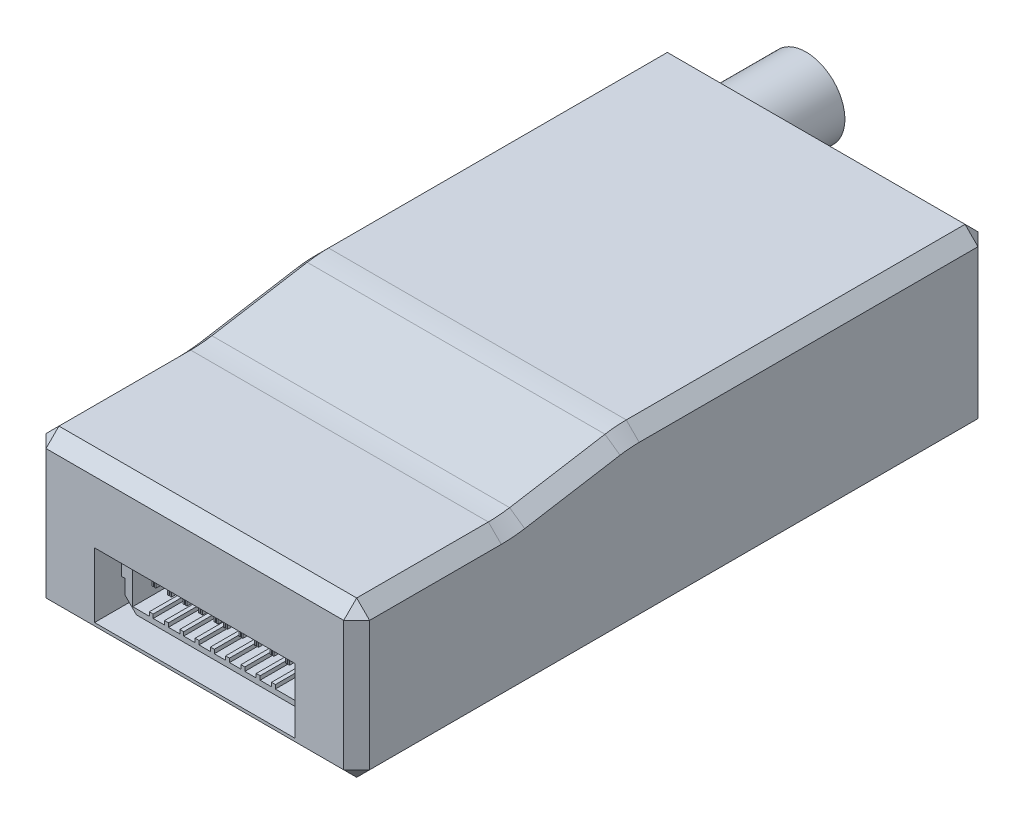
SolidWorks part; units mm, degrees
ref_plane "Front Plane" through (0, 0, 0) normal (0, 0, 1) x (1, 0, 0)
ref_plane "Top Plane" through (0, 0, 0) normal (0, 1, 0) x (1, 0, 0)
ref_plane "Right Plane" through (0, 0, 0) normal (1, 0, 0) x (0, 0, -1)
sketch "Sketch3" plane through (0, 0, 0) normal (1, 0, 0) x (0, 0, -1)
  line L0 (0, 0) -> (-49, 0)
  line L1 (0, 0) -> (0, 13.5)
  line L2 (-49, 0) -> (-49, 12)
  line L3 (-49, 12) -> (-37.8276, 12)
  line L4 (0, 13.5) -> (-27.1724, 13.5)
  line L5 (-36.1836, 12.1361) -> (-28.8164, 13.3639)
  arc A0 (-37.8276, 12) -> (-36.1836, 12.1361) centre (-37.8276, 22) ccw
  arc A1 (-27.1724, 13.5) -> (-28.8164, 13.3639) centre (-27.1724, 3.5) ccw
  point P9 (-37, 12)
  point P12 (-28, 13.5)
  dimension "D6" = 10
  dimension "D7" = 10
  dimension "D1" = 49
  dimension "D2" = 13.5
  dimension "D3" = 12
  dimension "D4" = 12
  dimension "D5" = 28
extrude "Boss-Extrude1" add sketch "Sketch3" along normal blind 25
chamfer "Chamfer1" distance 1 angle 45 20 edges at (0, 13.5, 13.5862) (25, 13.5, 13.5862) (0, 13.4659, 27.9972) (25, 13.4659, 27.9972) (0, 12.75, 32.5) (25, 12.75, 32.5) (0, 12.0341, 37.0028) (25, 12.0341, 37.0028) (12.5, 0, 0) (25, 6.75, 0) (12.5, 13.5, 0) (0, 6.75, 0) (0, 0, 24.5) (0, 12, 43.4138) (25, 0, 24.5) (25, 12, 43.4138) (12.5, 0, 49) (25, 6, 49) (0, 6, 49) (12.5, 12, 49)
sketch "Sketch4" plane through (0, 0, 49) normal (0, 0, 1) x (1, 0, 0)
  line L0 (12.5, 11) -> (12.5, 1) construction
  line L1 (24, 11) -> (1, 11) construction
  line L2 (1, 1) -> (24, 1) construction
  line L3 (4.75, 6.2316) -> (20.25, 6.2316)
  line L4 (20.25, 6.2316) -> (20.25, 1.2316)
  line L5 (20.25, 1.2316) -> (4.75, 1.2316)
  line L6 (4.75, 6.2316) -> (4.75, 1.2316)
  point P11 (12.5, 1.2316)
  point P12 (12.5, 6.2316)
  dimension "D1" = 15.5
  dimension "D2" = 5
extrude "Cut-Extrude1" cut sketch "Sketch4" against normal blind 10
sketch "Sketch5" plane through (0, 0, 39) normal (0, 0, 1) x (1, 0, 0)
  line L0 (12.5, 6.2316) -> (12.5, 1.2316) construction
  line L1 (20.25, 6.2316) -> (4.75, 6.2316) construction
  line L2 (4.75, 1.2316) -> (20.25, 1.2316) construction
  line L3 (20.1864, 6.1621) -> (4.8136, 6.1621)
  line L4 (8.1, 6.0621) -> (16.9, 6.0621)
  line L5 (16.9, 6.0621) -> (16.9, 4.5621)
  line L6 (19.0113, 1.3621) -> (19.9, 2.2507)
  line L7 (19.9, 2.2507) -> (19.9, 3.3621)
  line L8 (19.0113, 1.3621) -> (5.9887, 1.3621)
  line L9 (16.9, 4.5621) -> (15.5169, 4.5621)
  line L10 (15.5169, 4.5621) -> (15.0305, 4.7621)
  line L11 (15.0305, 4.7621) -> (9.9695, 4.7621)
  line L20 (19.9, 3.3621) -> (20.1864, 3.3621)
  line L21 (17.25, 5.6802) -> (18.25, 5.6802)
  line L22 (17.25, 5.6802) -> (17.25, 5.1302)
  line L23 (17.25, 5.1302) -> (18.25, 5.1302)
  line L24 (18.25, 5.6802) -> (18.25, 5.1302)
  line L25 (17.25, 5.6802) -> (18.25, 5.1302) construction
  line L26 (17.25, 5.1302) -> (18.25, 5.6802) construction
  line L31 (19.65, 5.1245) -> (18.65, 5.1245)
  line L32 (19.65, 5.1245) -> (19.65, 5.6745)
  line L33 (19.65, 5.6745) -> (18.65, 5.6745)
  line L34 (18.65, 5.1245) -> (18.65, 5.6745)
  line L35 (19.65, 5.1245) -> (18.65, 5.6745) construction
  line L36 (19.65, 5.6745) -> (18.65, 5.1245) construction
  line L37 (20.1864, 3.3621) -> (20.1864, 6.1621)
  line L38 (5.9887, 1.3621) -> (5.1, 2.2507)
  line L39 (5.1, 2.2507) -> (5.1, 3.3621)
  line L40 (5.1, 3.3621) -> (4.8136, 3.3621)
  line L41 (4.8136, 3.3621) -> (4.8136, 6.1621)
  line L42 (5.35, 5.1245) -> (5.35, 5.6745)
  line L43 (5.35, 5.1245) -> (6.35, 5.1245)
  line L44 (5.35, 5.6745) -> (6.35, 5.6745)
  line L45 (6.35, 5.1245) -> (6.35, 5.6745)
  line L46 (6.75, 5.6802) -> (6.75, 5.1302)
  line L47 (7.75, 5.1302) -> (6.75, 5.1302)
  line L48 (7.75, 5.6802) -> (6.75, 5.6802)
  line L49 (7.75, 5.6802) -> (7.75, 5.1302)
  line L50 (8.1, 6.0621) -> (8.1, 4.5621)
  line L51 (8.1, 4.5621) -> (9.4831, 4.5621)
  line L52 (9.4831, 4.5621) -> (9.9695, 4.7621)
  point P6 (12.5, 6.1621)
  point P9 (17.75, 5.4052)
  point P11 (12.5, 1.3621)
  point P17 (12.5, 6.0621)
  point P22 (19.15, 5.3995)
  point P23 (19.15, 5.3995)
  point P47 (12.5, 4.7621)
  dimension "D1" = 135
  dimension "D2" = 4.4
  dimension "D3" = 0.35
  dimension "D4" = 1
  dimension "D5" = 0.4
  dimension "D6" = 1
  dimension "D7" = 0.55
  dimension "D8" = 0.55
  dimension "D9" = 7.4
  dimension "D10" = 2
  dimension "D11" = 3.2
  dimension "D12" = 4.8
  dimension "D13" = 1.5
  dimension "D14" = 1.3
extrude "Boss-Extrude2" add sketch "Sketch5" along normal blind 8
sketch "Sketch6" plane through (0, 0, 47) normal (0, 0, 1) x (1, 0, 0)
  line L0 (12.5, 6.2316) -> (12.5, 1.3621) construction
  line L1 (20.25, 6.2316) -> (4.75, 6.2316) construction
  line L2 (5.9887, 1.3621) -> (19.0113, 1.3621) construction
  line L3 (12.29, 4.2671) -> (12.71, 4.2671)
  line L4 (18.18, 4.2671) -> (18.18, 4.4771)
  line L5 (18.18, 4.4771) -> (18.4, 4.4771)
  line L6 (18.4, 4.4771) -> (18.4, 4.2671)
  line L7 (18.4, 4.2671) -> (18.9, 4.2671)
  line L8 (18.9, 4.2671) -> (18.9, 4.7671)
  line L9 (18.9, 4.7671) -> (19.3, 4.7671)
  line L10 (19.3, 4.7671) -> (19.3, 1.7671)
  line L11 (19.3, 1.7671) -> (5.7, 1.7671)
  line L12 (12.71, 4.2671) -> (12.71, 3.8971)
  line L13 (12.71, 3.8971) -> (12.81, 3.8971)
  line L14 (12.81, 3.8971) -> (12.81, 4.2671)
  line L15 (12.91, 4.2671) -> (12.91, 3.8976)
  line L16 (12.91, 3.8976) -> (13.01, 3.8976)
  line L17 (13.01, 3.8976) -> (13.01, 4.2671)
  line L18 (13.91, 4.2671) -> (13.91, 3.8971)
  line L19 (13.91, 3.8971) -> (14.01, 3.8971)
  line L20 (14.01, 3.8971) -> (14.01, 4.2671)
  line L21 (14.11, 4.2671) -> (14.11, 3.8976)
  line L22 (14.11, 3.8976) -> (14.21, 3.8976)
  line L23 (14.21, 3.8976) -> (14.21, 4.2671)
  line L24 (15.11, 4.2671) -> (15.11, 3.8971)
  line L25 (15.11, 3.8971) -> (15.21, 3.8971)
  line L26 (15.21, 3.8971) -> (15.21, 4.2671)
  line L27 (15.31, 4.2671) -> (15.31, 3.8976)
  line L28 (15.31, 3.8976) -> (15.41, 3.8976)
  line L29 (15.41, 3.8976) -> (15.41, 4.2671)
  line L30 (16.31, 4.2671) -> (16.31, 3.8971)
  line L31 (16.31, 3.8971) -> (16.41, 3.8971)
  line L32 (16.41, 3.8971) -> (16.41, 4.2671)
  line L33 (16.51, 4.2671) -> (16.51, 3.8976)
  line L34 (16.51, 3.8976) -> (16.61, 3.8976)
  line L35 (16.61, 3.8976) -> (16.61, 4.2671)
  line L36 (17.51, 4.2671) -> (17.51, 3.8971)
  line L37 (17.51, 3.8971) -> (17.61, 3.8971)
  line L38 (17.61, 3.8971) -> (17.61, 4.2671)
  line L39 (17.71, 4.2671) -> (17.71, 3.8976)
  line L40 (17.71, 3.8976) -> (17.81, 3.8976)
  line L41 (17.81, 3.8976) -> (17.81, 4.2671)
  line L42 (12.81, 4.2671) -> (12.91, 4.2671)
  line L43 (13.01, 4.2671) -> (13.91, 4.2671)
  line L44 (14.01, 4.2671) -> (14.11, 4.2671)
  line L45 (14.21, 4.2671) -> (15.11, 4.2671)
  line L46 (15.21, 4.2671) -> (15.31, 4.2671)
  line L47 (15.41, 4.2671) -> (16.31, 4.2671)
  line L48 (16.41, 4.2671) -> (16.51, 4.2671)
  line L49 (16.61, 4.2671) -> (17.51, 4.2671)
  line L50 (17.61, 4.2671) -> (17.71, 4.2671)
  line L51 (17.81, 4.2671) -> (18.18, 4.2671)
  line L52 (5.7, 4.7671) -> (5.7, 1.7671)
  line L53 (6.1, 4.7671) -> (5.7, 4.7671)
  line L54 (6.1, 4.2671) -> (6.1, 4.7671)
  line L55 (6.6, 4.2671) -> (6.1, 4.2671)
  line L56 (6.6, 4.4771) -> (6.6, 4.2671)
  line L57 (6.82, 4.4771) -> (6.6, 4.4771)
  line L58 (6.82, 4.2671) -> (6.82, 4.4771)
  line L59 (7.19, 4.2671) -> (6.82, 4.2671)
  line L60 (7.19, 3.8976) -> (7.19, 4.2671)
  line L61 (7.29, 3.8976) -> (7.19, 3.8976)
  line L62 (7.29, 4.2671) -> (7.29, 3.8976)
  line L63 (7.39, 4.2671) -> (7.29, 4.2671)
  line L64 (7.39, 3.8971) -> (7.39, 4.2671)
  line L65 (7.49, 3.8971) -> (7.39, 3.8971)
  line L66 (7.49, 4.2671) -> (7.49, 3.8971)
  line L67 (8.39, 4.2671) -> (7.49, 4.2671)
  line L68 (8.39, 3.8976) -> (8.39, 4.2671)
  line L69 (8.49, 3.8976) -> (8.39, 3.8976)
  line L70 (8.49, 4.2671) -> (8.49, 3.8976)
  line L71 (8.59, 4.2671) -> (8.49, 4.2671)
  line L72 (8.59, 3.8971) -> (8.59, 4.2671)
  line L73 (8.69, 3.8971) -> (8.59, 3.8971)
  line L74 (8.69, 4.2671) -> (8.69, 3.8971)
  line L75 (9.59, 4.2671) -> (8.69, 4.2671)
  line L76 (9.59, 3.8976) -> (9.59, 4.2671)
  line L77 (9.69, 3.8976) -> (9.59, 3.8976)
  line L78 (9.69, 4.2671) -> (9.69, 3.8976)
  line L79 (9.79, 4.2671) -> (9.69, 4.2671)
  line L80 (9.79, 3.8971) -> (9.79, 4.2671)
  line L81 (9.89, 3.8971) -> (9.79, 3.8971)
  line L82 (9.89, 4.2671) -> (9.89, 3.8971)
  line L83 (10.79, 4.2671) -> (9.89, 4.2671)
  line L84 (10.79, 3.8976) -> (10.79, 4.2671)
  line L85 (10.89, 3.8976) -> (10.79, 3.8976)
  line L86 (10.89, 4.2671) -> (10.89, 3.8976)
  line L87 (10.99, 4.2671) -> (10.89, 4.2671)
  line L88 (10.99, 3.8971) -> (10.99, 4.2671)
  line L89 (11.09, 3.8971) -> (10.99, 3.8971)
  line L90 (11.09, 4.2671) -> (11.09, 3.8971)
  line L91 (11.99, 4.2671) -> (11.09, 4.2671)
  line L92 (11.99, 3.8976) -> (11.99, 4.2671)
  line L93 (12.09, 3.8976) -> (11.99, 3.8976)
  line L94 (12.09, 4.2671) -> (12.09, 3.8976)
  line L95 (12.19, 4.2671) -> (12.09, 4.2671)
  line L96 (12.19, 3.8971) -> (12.19, 4.2671)
  line L97 (12.29, 3.8971) -> (12.19, 3.8971)
  line L98 (12.29, 4.2671) -> (12.29, 3.8971)
  point P57 (12.5, 1.7671)
  point P104 (12.5, 4.2671)
  dimension "D1" = 0.21
  dimension "D2" = 0.22
  dimension "D3" = 0.21
  dimension "D4" = 0.5
  dimension "D5" = 0.4
  dimension "D6" = 0.5
  dimension "D7" = 3
  dimension "D8" = 6.8
  dimension "D9" = 0.21
  dimension "D10" = 0.1
  dimension "D11" = 0.37
  dimension "D12" = 0.1
  dimension "D13" = 0.1
  dimension "D14" = 5
extrude "Cut-Extrude2" cut sketch "Sketch6" against normal blind 10
sketch "Sketch7" plane through (0, 0, 47) normal (0, 0, 1) x (1, 0, 0)
  line L0 (5.7, 1.7671) -> (19.3, 1.7671) construction
  line L1 (5.7, 1.7671) -> (19.3, 1.7671)
  line L2 (19.3, 1.7671) -> (19.3, 4.7671) construction
  line L3 (17.9, 1.7671) -> (17.6, 1.7671)
  line L4 (17.9, 1.7671) -> (17.9, 2.0671)
  line L5 (17.9, 2.0671) -> (17.6, 2.0671)
  line L6 (17.6, 1.7671) -> (17.6, 2.0671)
  line L7 (19.3, 1.7671) -> (19.3, 4.7671) construction
  line L8 (16.42, 1.7671) -> (16.42, 2.0671)
  line L9 (16.72, 2.0671) -> (16.42, 2.0671)
  line L10 (16.72, 1.7671) -> (16.72, 2.0671)
  line L11 (15.24, 1.7671) -> (15.24, 2.0671)
  line L12 (15.54, 2.0671) -> (15.24, 2.0671)
  line L13 (15.54, 1.7671) -> (15.54, 2.0671)
  line L14 (14.06, 1.7671) -> (14.06, 2.0671)
  line L15 (14.36, 2.0671) -> (14.06, 2.0671)
  line L16 (14.36, 1.7671) -> (14.36, 2.0671)
  line L17 (12.88, 1.7671) -> (12.88, 2.0671)
  line L18 (13.18, 2.0671) -> (12.88, 2.0671)
  line L19 (13.18, 1.7671) -> (13.18, 2.0671)
  line L20 (11.7, 1.7671) -> (11.7, 2.0671)
  line L21 (12, 2.0671) -> (11.7, 2.0671)
  line L22 (12, 1.7671) -> (12, 2.0671)
  line L23 (10.52, 1.7671) -> (10.52, 2.0671)
  line L24 (10.82, 2.0671) -> (10.52, 2.0671)
  line L25 (10.82, 1.7671) -> (10.82, 2.0671)
  line L26 (9.34, 1.7671) -> (9.34, 2.0671)
  line L27 (9.64, 2.0671) -> (9.34, 2.0671)
  line L28 (9.64, 1.7671) -> (9.64, 2.0671)
  line L29 (8.16, 1.7671) -> (8.16, 2.0671)
  line L30 (8.46, 2.0671) -> (8.16, 2.0671)
  line L31 (8.46, 1.7671) -> (8.46, 2.0671)
  line L32 (6.98, 1.7671) -> (6.98, 2.0671)
  line L33 (7.28, 2.0671) -> (6.98, 2.0671)
  line L34 (7.28, 1.7671) -> (7.28, 2.0671)
  dimension "D1" = 1.4
  dimension "D2" = 1.7
  dimension "D3" = 0.3
  dimension "D4" = 10
extrude "Boss-Extrude3" add sketch "Sketch7" against normal blind 10 contours L1 L34 L33 L32 | L1 L31 L30 L29 | L1 L28 L27 L26 | L1 L25 L24 L23 | L1 L22 L21 L20 | L1 L19 L18 L17 | L1 L16 L15 L14 | L1 L13 L12 L11 | L1 L10 L9 L8
sketch "Sketch8" plane through (0, 0, 0) normal (0, 0, -1) x (-1, 0, 0)
  circle A0 centre (-4.7147, 8.8868) radius 3
  circle A1 centre (-4.7147, 8.8868) radius 2.5
  dimension "D1" = 6
  dimension "D2" = 5
extrude "Boss-Extrude4" add sketch "Sketch8" along normal blind 6
